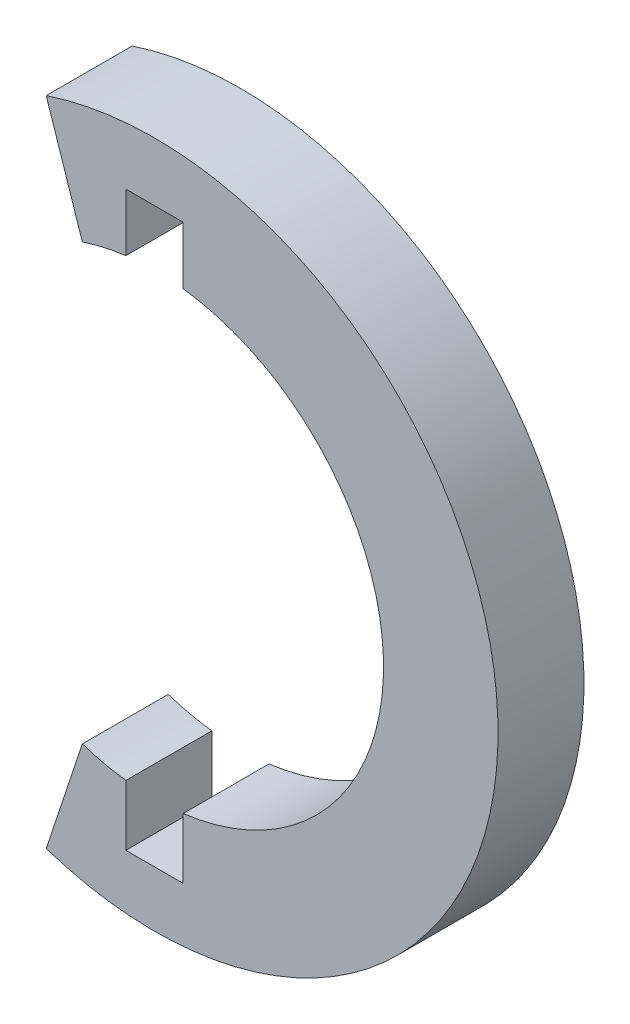
SolidWorks part; units mm, degrees
ref_plane "Front Plane" through (0, 0, 0) normal (0, 0, 1) x (1, 0, 0)
ref_plane "Top Plane" through (0, 0, 0) normal (0, 1, 0) x (1, 0, 0)
ref_plane "Right Plane" through (0, 0, 0) normal (1, 0, 0) x (0, 0, -1)
sketch "Sketch2" plane through (0, 0, 0) normal (0, 0, 1) x (1, 0, 0)
  line L0 (-3.7817, 11.3885) -> (-2.5211, 7.5924)
  line L1 (-2.5211, -7.5924) -> (-3.7817, -11.3885)
  line L2 (1, 8.9443) -> (1, 9.9499)
  line L3 (1, 9.9499) -> (-1, 9.9499)
  line L4 (-1, 8.9443) -> (-1, 9.9499)
  line L5 (0, -11.1003) -> (0, -10.0501) construction
  line L6 (-1, -8.9443) -> (-1, -7.9373)
  line L7 (1, -10.0501) -> (-1, -10.0501)
  line L8 (-1, -8.9443) -> (-1, -10.0501)
  line L9 (1, -8.9443) -> (1, -7.9373)
  line L10 (1, -8.9443) -> (1, -10.0501)
  line L11 (0, 9.9499) -> (0, 10.8997) construction
  line L12 (-1, 8.9443) -> (-1, 7.9373)
  line L13 (1, 8.9443) -> (1, 7.9373)
  arc A2 (1, -7.9373) -> (1, 7.9373) centre (0, 0) ccw
  arc A8 (-3.7817, -11.3885) -> (-3.7817, 11.3885) centre (0, 0) ccw
  arc A9 (-2.5211, -7.5924) -> (-1, -7.9373) centre (0, 0) ccw
  arc A10 (-1, 7.9373) -> (-2.5211, 7.5924) centre (0, 0) ccw
  point P7 (0, 9)
  dimension "D1" = 4
  dimension "D2" = 20
  dimension "D4" = 2
extrude "Boss-Extrude1" add sketch "Sketch2" along normal blind 3
